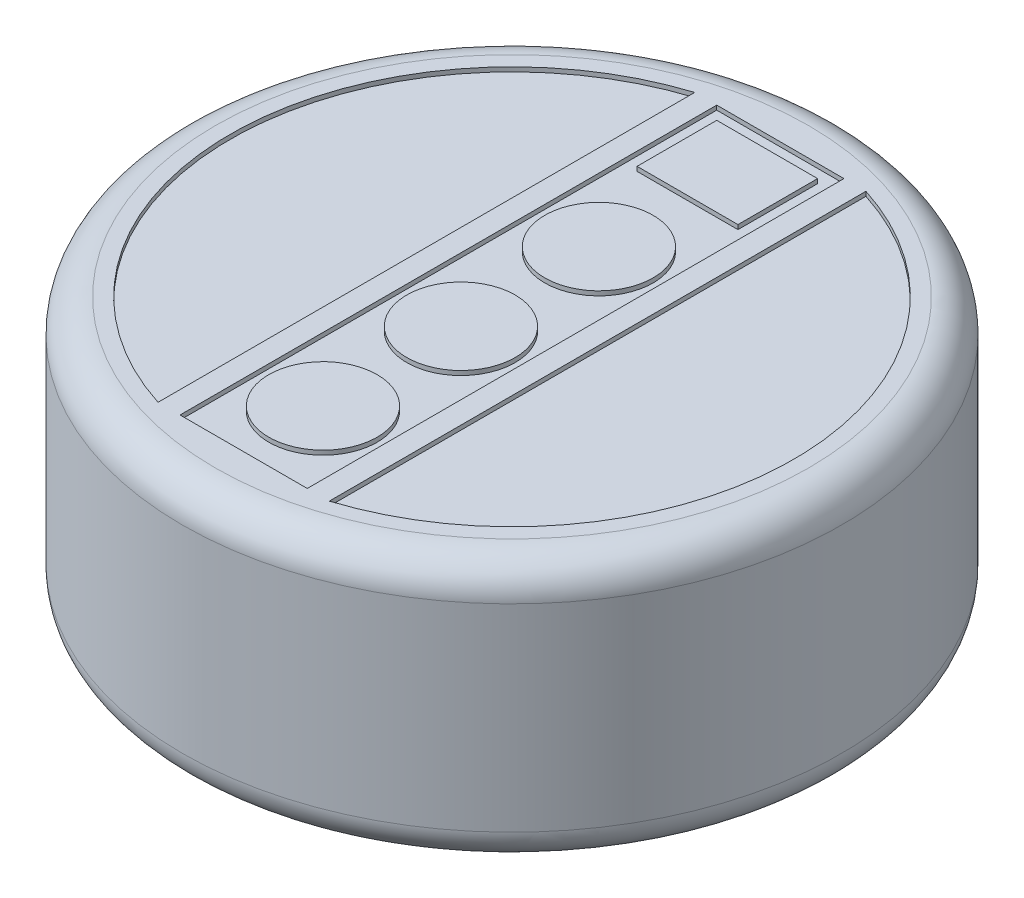
SolidWorks part; units mm, degrees
ref_plane "Front Plane" through (0, 0, 0) normal (0, 0, 1) x (1, 0, 0)
ref_plane "Top Plane" through (0, 0, 0) normal (0, 1, 0) x (1, 0, 0)
ref_plane "Right Plane" through (0, 0, 0) normal (1, 0, 0) x (0, 0, -1)
sketch "Sketch1" plane through (0, 0, 0) normal (0, 1, 0) x (1, 0, 0)
  circle A0 centre (0, 0) radius 190.5
  dimension "D1" = 381
extrude "Boss-Extrude1" add sketch "Sketch1" along normal blind 152.4 contours A0
sketch "Sketch4" plane through (0, 152.4, 0) normal (0, 1, 0) x (1, 0, 0)
  line L0 (0, 0) -> (0, 53.9768) construction
  line L1 (-49.4787, 155.1178) -> (-49.4787, -155.1178)
  line L2 (49.4787, 155.1178) -> (49.4787, -155.1178)
  line L4 (-36.7787, 155.1178) -> (36.7787, 155.1178)
  line L5 (-36.7787, 155.1178) -> (-36.7787, -155.1178)
  line L6 (-36.7787, -155.1178) -> (36.7787, -155.1178)
  line L7 (36.7787, 155.1178) -> (36.7787, -155.1178)
  arc A0 (-49.4787, 155.1178) -> (-49.4787, -155.1178) centre (0, 0) ccw
  arc A1 (49.4787, 155.1178) -> (49.4787, -155.1178) centre (0, 0) cw
  dimension "D1" = 12.7
  dimension "D2" = 12.7
extrude "Cut-Extrude2" cut sketch "Sketch4" against normal blind 2.54
sketch "Sketch5" plane through (0, 149.86, 0) normal (0, 1, 0) x (1, 0, 0)
  line L0 (0, 0) -> (50000, 0) construction
  line L1 (0, 0) -> (0, 50000) construction
  line L2 (-36.7787, 155.1178) -> (-36.7787, -155.1178) construction
  line L3 (-29.1587, 147.4978) -> (29.1587, 147.4978)
  line L4 (-29.1587, 147.4978) -> (-29.1587, 101.4563)
  line L5 (-29.1587, 101.4563) -> (29.1587, 101.4563)
  line L6 (29.1587, 147.4978) -> (29.1587, 101.4563)
  line L7 (36.7787, -155.1178) -> (36.7787, 155.1178) construction
  line L8 (36.7787, 155.1178) -> (-36.7787, 155.1178) construction
  circle A0 centre (0, 50.2503) radius 31.3345
  circle A1 centre (0, -29.5057) radius 31.3345
  circle A5 centre (0, -109.2617) radius 31.3345
  dimension "D4" = 79.756
  dimension "D1" = 7.62
  dimension "D2" = 7.62
  dimension "D3" = 7.62
  dimension "D5" = 79.756
extrude "Boss-Extrude3" add sketch "Sketch5" along normal blind 2.54
sketch "Sketch6" plane through (0, 0, 0) normal (0, -1, 0) x (1, 0, 0)
  line L1 (-166.4283, 34.4852) -> (-141.0283, 34.4852)
  line L2 (-166.4283, 34.4852) -> (-166.4283, -29.0148)
  line L3 (-166.4283, -29.0148) -> (-141.0283, -29.0148)
  line L4 (-141.0283, 34.4852) -> (-141.0283, -29.0148)
  line L5 (139.44, 34.0127) -> (164.84, 34.0127)
  line L6 (139.44, 34.0127) -> (139.44, -29.4873)
  line L7 (139.44, -29.4873) -> (164.84, -29.4873)
  line L8 (164.84, 34.0127) -> (164.84, -29.4873)
  dimension "D1" = 25.4
  dimension "D2" = 63.5
sketch "Sketch7" plane through (0, 149.86, 0) normal (0, 1, 0) x (1, 0, 0)
extrude "Cut-Extrude3" cut sketch "Sketch6" against normal blind 38.1
fillet "Fillet3" radius 19.05 2 edges at (0, 0, 190.5) (0, 152.4, 190.5)
sketch "Sketch8" plane through (0, 0, 0) normal (0, -1, 0) x (1, 0, 0)
  line L0 (0, 0) -> (0, 148.7941) construction
  line L2 (-96.0757, 70.4555) -> (96.0757, 70.4555)
  line L3 (-96.0757, 70.4555) -> (-96.0757, 104.9442)
  line L4 (-96.0757, 104.9442) -> (96.0757, 104.9442)
  line L5 (96.0757, 70.4555) -> (96.0757, 104.9442)
  line L6 (-96.0757, 70.4555) -> (96.0757, 104.9442) construction
  line L7 (-96.0757, 104.9442) -> (96.0757, 70.4555) construction
  point P1 (0, 87.6998)
extrude "Cut-Extrude4" cut sketch "Sketch8" against normal blind 25.4
